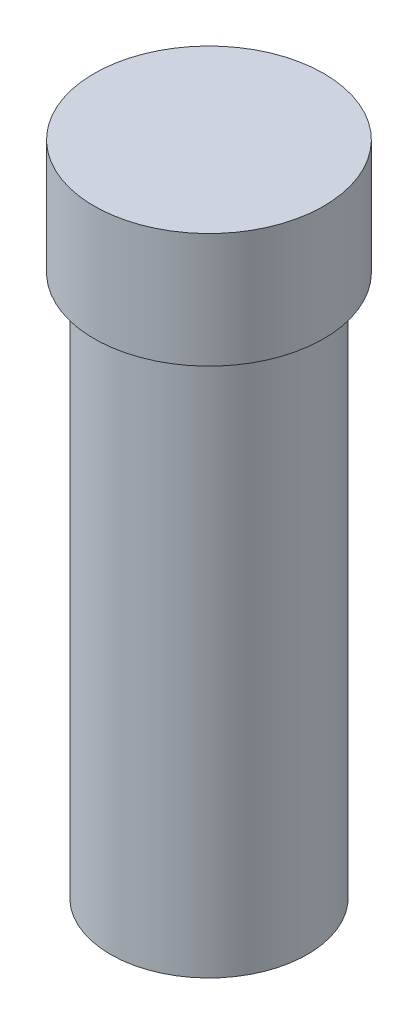
SolidWorks part; units mm, degrees
ref_plane "Front Plane" through (0, 0, 0) normal (0, 0, 1) x (1, 0, 0)
ref_plane "Top Plane" through (0, 0, 0) normal (0, 1, 0) x (1, 0, 0)
ref_plane "Right Plane" through (0, 0, 0) normal (1, 0, 0) x (0, 0, -1)
sketch "Sketch1" plane through (0, 0, 0) normal (0, 0, 1) x (1, 0, 0)
  line L0 (0, 0) -> (0, 40)
  line L1 (0, 40) -> (7, 40)
  line L2 (7, 40) -> (7, 33)
  line L3 (7, 33) -> (6, 33)
  line L4 (6, 33) -> (6, 0)
  line L5 (6, 0) -> (0, 0)
  dimension "D1" = 7
  dimension "D2" = 6
  dimension "D3" = 7
  dimension "D4" = 40
revolve "Revolve1" add sketch "Sketch1" angle 360 about L0
